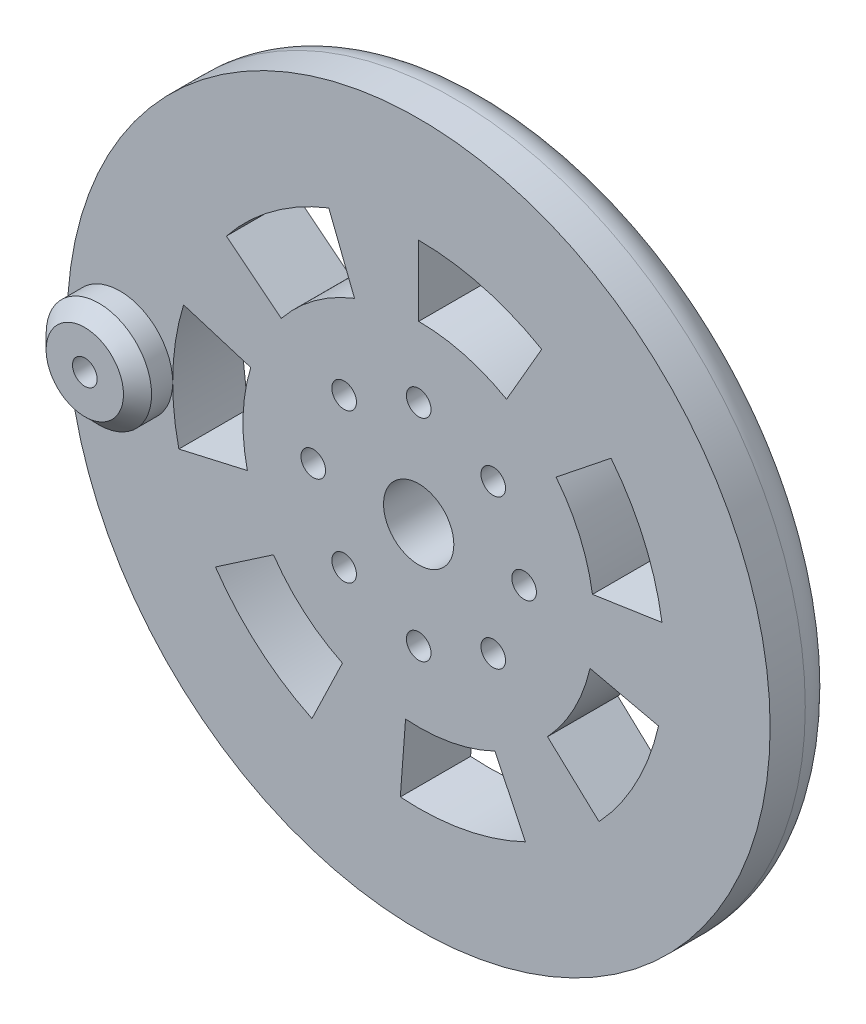
SolidWorks part; units mm, degrees
ref_plane "Front Plane" through (0, 0, 0) normal (0, 0, 1) x (1, 0, 0)
ref_plane "Top Plane" through (0, 0, 0) normal (0, 1, 0) x (1, 0, 0)
ref_plane "Right Plane" through (0, 0, 0) normal (1, 0, 0) x (0, 0, -1)
sketch "Sketch1" plane through (0, 0, 0) normal (0, 0, 1) x (1, 0, 0)
  circle A0 centre (0, 0) radius 50
  dimension "D1" = 100
extrude "Boss-Extrude1" add sketch "Sketch1" along normal blind 10
sketch "Sketch2" plane through (0, 0, 10) normal (0, 0, 1) x (1, 0, 0)
  circle A0 centre (0, 0) radius 5
extrude "Cut-Extrude1" cut sketch "Sketch2" against normal through all
fillet "Fillet1" radius 5 1 edges at (50, 0, 0)
sketch "Sketch3" plane through (0, 0, 0) normal (0, 0, -1) x (-1, 0, 0)
  line L0 (0, 0) -> (0, 15) construction
  circle A0 centre (0, 15) radius 1.75
  circle A1 centre (10.6066, 10.6066) radius 1.75
  circle A2 centre (15, 0) radius 1.75
  circle A3 centre (10.6066, -10.6066) radius 1.75
  circle A4 centre (0, -15) radius 1.75
  circle A5 centre (-10.6066, -10.6066) radius 1.75
  circle A6 centre (-15, 0) radius 1.75
  circle A7 centre (-10.6066, 10.6066) radius 1.75
  point P21 (0, 0)
  dimension "D1" = 3.5
  dimension "D2" = 15
  dimension "D3" = 8
extrude "Cut-Extrude2" cut sketch "Sketch3" against normal through all
sketch "Sketch5" plane through (0, 0, 10) normal (0, 0, 1) x (1, 0, 0)
  line L0 (-42.5, 0) -> (0, 0) construction
  circle A0 centre (-42.5, 0) radius 7.5
  circle A1 centre (0, 0) radius 50 construction
  dimension "D1" = 15
extrude "Boss-Extrude2" add sketch "Sketch5" along normal blind 5
sketch "Sketch6" plane through (0, 0, 15) normal (0, 0, 1) x (1, 0, 0)
  circle A0 centre (-42.5, 0) radius 1.75
  dimension "D1" = 3.5
extrude "Cut-Extrude3" cut sketch "Sketch6" against normal through all
sketch "Sketch7" plane through (0, 0, 0) normal (0, 0, -1) x (-1, 0, 0)
  circle A0 centre (42.5, 0) radius 5.94
extrude "Cut-Extrude4" cut sketch "Sketch7" against normal blind 5
chamfer "Chamfer1" distance 2 angle 45 1 edges at (-48.44, 0, 5)
chamfer "Chamfer2" distance 2 angle 45 1 edges at (-35, 0, 15)
sketch "Sketch8" plane through (0, 0, 10) normal (0, 0, 1) x (1, 0, 0)
  line L0 (0, 35) -> (0, 25)
  line L1 (12.5, 21.6506) -> (17.5, 30.3109)
  line L2 (12.5, 21.6506) -> (0, 0) construction
  arc A0 (0, 25) -> (12.5, 21.6506) centre (0, 0) cw
  arc A1 (0, 35) -> (17.5, 30.3109) centre (0, 0) cw
  dimension "D1" = 25
  dimension "D2" = 35
  dimension "D3" = 30
extrude "Cut-Extrude5" cut sketch "Sketch8" against normal through all
pattern_circular "CirPattern1" count 7 over 360 about axis through (0, 0, 0) along (0, 0, 1) of "Cut-Extrude5"
